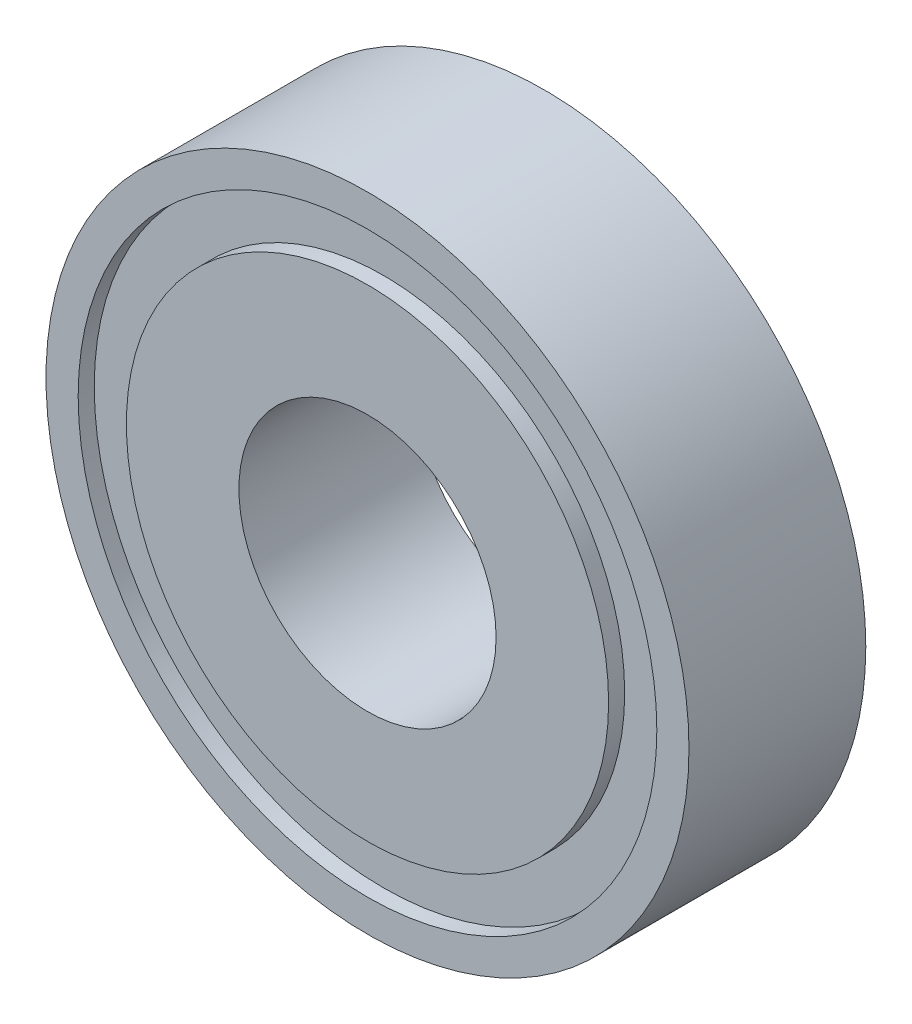
SolidWorks part; units mm, degrees
ref_plane "前视基准面" through (0, 0, 0) normal (0, 0, 1) x (1, 0, 0)
ref_plane "上视基准面" through (0, 0, 0) normal (0, 1, 0) x (1, 0, 0)
ref_plane "右视基准面" through (0, 0, 0) normal (1, 0, 0) x (0, 0, -1)
sketch "草图1" plane through (0, 0, 0) normal (0, 0, 1) x (1, 0, 0)
  circle A0 centre (0, 0) radius 8
  circle A1 centre (0, 0) radius 20
extrude "凸台-拉伸1" add sketch "草图1" along normal blind 11
sketch "草图2" plane through (0, 0, 11) normal (0, 0, 1) x (1, 0, 0)
  circle A0 centre (0, 0) radius 15
  circle A1 centre (0, 0) radius 18
extrude "切除-拉伸1" cut sketch "草图2" against normal blind 1
